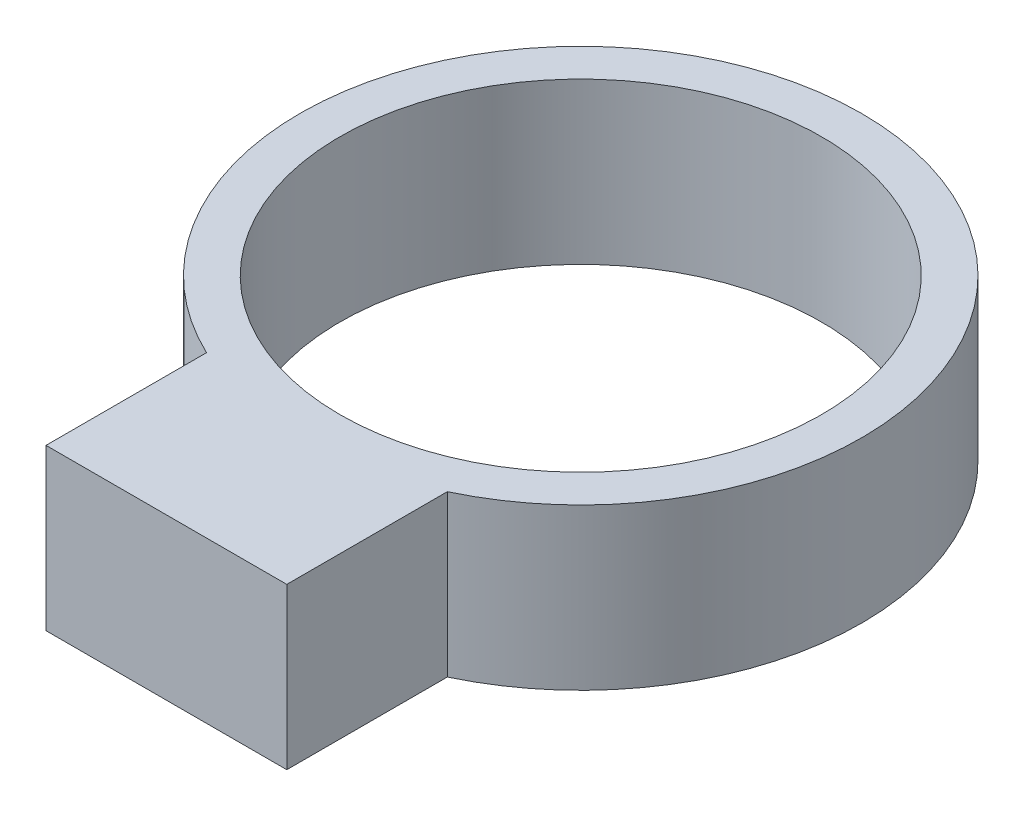
SolidWorks part; units mm, degrees
ref_plane "Front Plane" through (0, 0, 0) normal (0, 0, 1) x (1, 0, 0)
ref_plane "Top Plane" through (0, 0, 0) normal (0, 1, 0) x (1, 0, 0)
ref_plane "Right Plane" through (0, 0, 0) normal (1, 0, 0) x (0, 0, -1)
sketch "Sketch1" plane through (0, 0, 0) normal (0, 1, 0) x (1, 0, 0)
  line L1 (-7.5, -25.8114) -> (7.5, -25.8114)
  line L2 (-7.5, -25.8114) -> (-7.5, -15.8114)
  line L4 (7.5, -25.8114) -> (7.5, -15.8114)
  circle A0 centre (0, 0) radius 15
  arc A1 (7.5, -15.8114) -> (-7.5, -15.8114) centre (0, 0) ccw
  dimension "D1" = 30
  dimension "D2" = 35
  dimension "D3" = 15
  dimension "D4" = 10
extrude "Boss-Extrude1" add sketch "Sketch1" along normal blind 10
